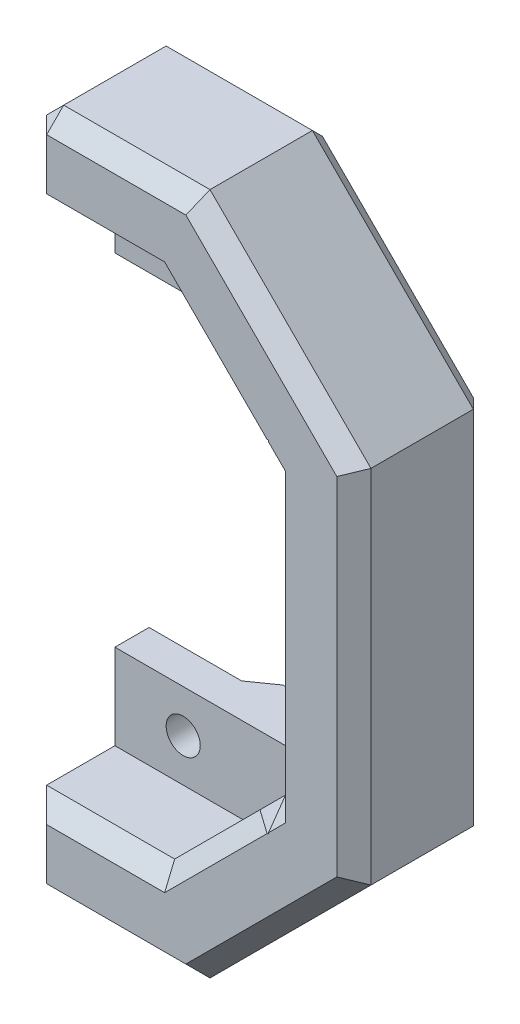
SolidWorks part; units mm, degrees
material "PET"
ref_plane "前视基准面" through (0, 0, 0) normal (0, 0, 1) x (1, 0, 0)
ref_plane "上视基准面" through (0, 0, 0) normal (0, 1, 0) x (1, 0, 0)
ref_plane "右视基准面" through (0, 0, 0) normal (1, 0, 0) x (0, 0, -1)
sketch "草图1" plane through (0, 0, 0) normal (0, 0, 1) x (1, 0, 0)
  line L0 (0, 0) -> (0, 8.5)
  line L1 (0, 8.5) -> (-6.5, 15)
  line L2 (-6.5, 15) -> (-14, 15)
  line L3 (-5, 0) -> (-5, 6.4289)
  line L4 (-5, 6.4289) -> (-8.5711, 10)
  line L5 (-8.5711, 10) -> (-14, 10)
  line L6 (-14, 15) -> (-14, 10)
  line L7 (-1000, 0) -> (49000, 0) construction
  line L8 (0, 0) -> (0, -8.5)
  line L9 (-5, 0) -> (-5, -6.4289)
  line L10 (-5, -6.4289) -> (-8.5711, -10)
  line L11 (-6.5, -15) -> (-14, -15)
  line L12 (-14, -15) -> (-14, -10)
  line L13 (0, -8.5) -> (-6.5, -15)
  line L14 (-8.5711, -10) -> (-14, -10)
  line L15 (-4.4289, 20) -> (-19, 20) construction
  line L16 (-19, 20) -> (-19, 5) construction
  line L17 (-10.6421, 5) -> (-19, 5) construction
  line L18 (-10, 4.3579) -> (-10.6421, 5) construction
  line L19 (-10, 0) -> (-10, 4.3579) construction
  line L20 (-10, 0) -> (-10, -4.3579) construction
  line L21 (-10, -4.3579) -> (-10.6421, -5) construction
  line L22 (-10.6421, -5) -> (-19, -5) construction
  line L23 (-19, -20) -> (-19, -5) construction
  line L24 (-4.4289, -20) -> (-19, -20) construction
  line L25 (5, -10.5711) -> (-4.4289, -20)
  line L26 (5, 0) -> (5, -10.5711)
  line L27 (5, 0) -> (5, 10.5711)
  line L28 (5, 10.5711) -> (-4.4289, 20)
  line L29 (-4.4289, 20) -> (-14, 20)
  line L30 (-14, 20) -> (-14, 15)
  line L31 (-14, -20) -> (-14, -15)
  line L32 (-4.4289, -20) -> (-14, -20)
  dimension "D1" = 6.5
  dimension "D2" = 6.5
  dimension "D3" = 15
  dimension "D4" = 7.5
  dimension "D5" = 5
  dimension "D6" = 5
extrude "凸台-拉伸1" add sketch "草图1" along normal blind 3 contours L10 L14 L12 L11 L13 L8 L0 L1 L2 L6 L5 L4 L3 L9 | L32 L25 L26 L27 L28 L29 L30 L2 L1 L0 L8 L13 L11 L31
sketch "草图3" plane through (0, 0, 3) normal (0, 0, 1) x (1, 0, 0)
  line L0 (-14, -20) -> (-14, -15) construction
  line L1 (-4.4289, -20) -> (-14, -20) construction
  line L2 (-6.5, -15) -> (-14, -15) construction
  line L3 (0, -8.5) -> (-6.5, -15) construction
  line L4 (5, -10.5711) -> (-4.4289, -20) construction
  line L5 (5, 0) -> (5, -10.5711) construction
  line L6 (5, 0) -> (5, 10.5711) construction
  line L7 (0, 0) -> (0, -8.5) construction
  line L8 (0, 0) -> (0, 8.5) construction
  line L9 (5, 10.5711) -> (-4.4289, 20) construction
  line L10 (0, 8.5) -> (-6.5, 15) construction
  line L11 (-6.5, 15) -> (-14, 15) construction
  line L12 (-14, 20) -> (-14, 15) construction
  line L13 (-4.4289, 20) -> (-14, 20) construction
  line L14 (-14, -20) -> (-14, -15)
  line L15 (-4.4289, -20) -> (-14, -20)
  line L16 (-6.5, -15) -> (-14, -15)
  line L17 (0, -8.5) -> (-6.5, -15)
  line L18 (5, -10.5711) -> (-4.4289, -20)
  line L19 (5, 0) -> (5, -10.5711)
  line L20 (5, 0) -> (5, 10.5711)
  line L21 (0, 0) -> (0, -8.5)
  line L22 (0, 0) -> (0, 8.5)
  line L23 (5, 10.5711) -> (-4.4289, 20)
  line L24 (0, 8.5) -> (-6.5, 15)
  line L25 (-6.5, 15) -> (-14, 15)
  line L26 (-14, 20) -> (-14, 15)
  line L27 (-4.4289, 20) -> (-14, 20)
extrude "凸台-拉伸2" add sketch "草图3" along normal blind 5
sketch "草图4" plane through (0, 0, 3) normal (0, 0, 1) x (1, 0, 0)
  line L0 (-14, 15) -> (-14, 10) construction
  line L1 (-14, -15) -> (-14, -10) construction
  line L2 (-8.5711, 10) -> (-14, 10) construction
  line L3 (-8.5711, -10) -> (-14, -10) construction
  line L5 (-5, 6.4289) -> (-8.5711, 10) construction
  line L6 (-5, 6.4289) -> (-8.5711, 10) construction
  line L7 (-6.7855, 8.2145) -> (-5.0178, 9.9822) construction
  line L8 (-1000, 0) -> (49000, 0) construction
  circle A0 centre (-10, 12.5) radius 1
  circle A2 centre (-10, -12.5) radius 1
  circle A3 centre (-5.0178, 9.9822) radius 1 construction
  circle A4 centre (-5.0178, -9.9822) radius 1 construction
  dimension "D2" = 2
  dimension "D3" = 2
  dimension "D7" = 2
  dimension "D1" = 4
  dimension "D4" = 4
  dimension "D5" = 2.5
  dimension "D6" = 2.5
  dimension "D8" = 2.5
extrude "切除-拉伸1" cut sketch "草图4" against normal blind 8
chamfer "倒角1" distance 1 angle 45 26 edges at (-9.2145, 20, 0) (-9.2145, 20, 8) (0.2855, 15.2855, 0) (0.2855, 15.2855, 8) (5, 0, 0) (5, 0, 8) (0.2855, -15.2855, 0) (0.2855, -15.2855, 8) (-9.2145, -20, 0) (-9.2145, -20, 8) (-14, -15, 0) (-14, -20, 4) (-14, -17.5, 8) (-14, 15, 0) (-14, 20, 4) (-14, 17.5, 8) (-11.2855, -10, 0) (-6.7855, -8.2145, 0) (-5, 0, 0) (-6.7855, 8.2145, 0) (-11.2855, 10, 0) (-10.25, -15, 8) (-3.25, -11.75, 8) (0, 0, 8) (-3.25, 11.75, 8) (-10.25, 15, 8)
sketch "草图5" plane through (0, 0, 0) normal (0, 0, -1) x (-1, 0, 0)
  line L0 (-4, 10.1569) -> (11, 10.1569) construction
  line L1 (11, 10.1569) -> (11, -10.1569)
  line L2 (11, -10.1569) -> (-4, -10.1569) construction
  line L3 (1, 10.1569) -> (1, -10.1569)
  line L5 (-4, 10.1569) -> (-4, -10.1569) construction
  dimension "D1" = 5
  dimension "D2" = 10
sketch "草图6" plane through (0, 0, 0) normal (0, 0, -1) x (-1, 0, 0)
  line L0 (8.5711, 10) -> (0, 10)
  line L1 (0, 10) -> (0, -10)
  line L2 (0, -10) -> (8.5711, -10)
  line L4 (-5, -10.5711) -> (-5, 10.5711) construction
  dimension "D1" = 5
extrude "切除-拉伸3" cut sketch "草图6" against normal through all and the other way through all
